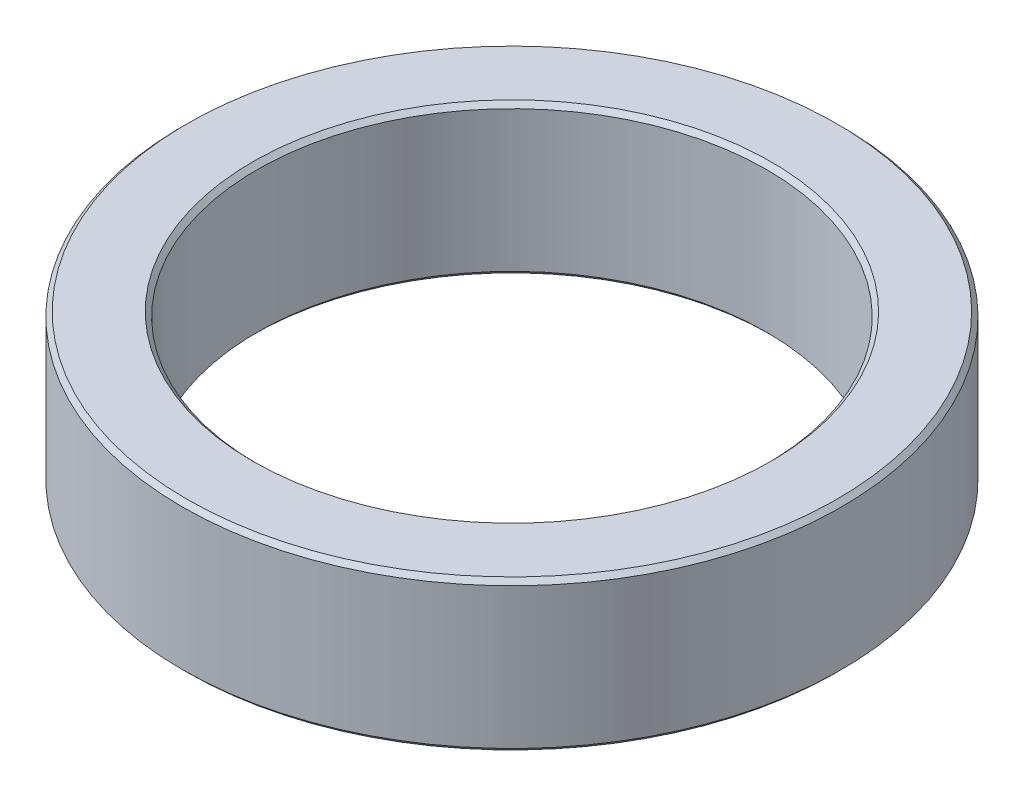
SolidWorks part; units mm, degrees
ref_plane "Front Plane" through (0, 0, 0) normal (0, 0, 1) x (1, 0, 0)
ref_plane "Top Plane" through (0, 0, 0) normal (0, 1, 0) x (1, 0, 0)
ref_plane "Right Plane" through (0, 0, 0) normal (1, 0, 0) x (0, 0, -1)
sketch "Sketch1" plane through (0, 0, 0) normal (0, 1, 0) x (1, 0, 0)
  circle A0 centre (0, 0) radius 8.5
  circle A1 centre (0, 0) radius 10.995
  dimension "D1" = 21.99
  dimension "D2" = 17
extrude "Boss-Extrude1" add sketch "Sketch1" along normal blind 5
chamfer "Chamfer1" distance 0.15 angle 45 4 edges at (0, 0, 8.5) (0, 5, 8.5) (0, 0, 10.995) (0, 5, 10.995)
